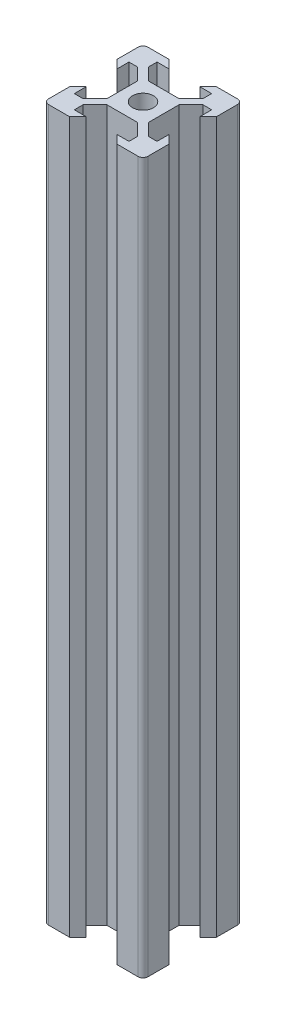
SolidWorks part; units mm, degrees
material "1060 Alloy"
ref_plane "Front Plane" through (0, 0, 0) normal (0, 0, 1) x (1, 0, 0)
ref_plane "Top Plane" through (0, 0, 0) normal (0, 1, 0) x (1, 0, 0)
ref_plane "Right Plane" through (0, 0, 0) normal (1, 0, 0) x (0, 0, -1)
ref_plane "End Plane" through (0, 143, 0) normal (0, 1, 0) x (1, 0, 0)
sketch "MasterLayoutSketch" plane through (0, 0, 0) normal (0, 1, 0) x (1, 0, 0)
  line L0 (-8.325, 3.1) -> (-8.325, 5.5)
  line L1 (-10, -10) -> (10, -10) construction
  line L2 (-10, -10) -> (-10, 10) construction
  line L3 (-10, 10) -> (10, 10) construction
  line L4 (10, -10) -> (10, 10) construction
  line L5 (-10, -10) -> (10, 10) construction
  line L6 (-10, 10) -> (10, -10) construction
  line L7 (-4.775, 10) -> (-3.1, 8.325)
  line L10 (-8.325, 5.5) -> (-6.5607, 5.5)
  line L11 (-10, 4.775) -> (-8.325, 3.1)
  line L12 (-5.5, 8.325) -> (-5.5, 6.5607)
  line L13 (-3.1, 8.325) -> (-5.5, 8.325)
  line L14 (-10, 10) -> (-10, 4.775)
  line L19 (3.1, 8.325) -> (5.5, 8.325)
  line L20 (10, 4.775) -> (8.325, 3.1)
  line L21 (-10, 10) -> (-4.775, 10)
  line L22 (-6.5607, 5.5) -> (-4.1607, 3.1)
  line L23 (-5.5, 6.5607) -> (-3.1, 4.1607)
  line L24 (5.5, 8.325) -> (5.5, 6.5607)
  line L25 (4.775, 10) -> (3.1, 8.325)
  line L26 (8.325, 5.5) -> (6.5607, 5.5)
  line L27 (8.325, 3.1) -> (8.325, 5.5)
  line L28 (10, 10) -> (4.775, 10)
  line L29 (10, 10) -> (10, 4.775)
  line L30 (5.5, 6.5607) -> (3.1, 4.1607)
  line L31 (6.5607, 5.5) -> (4.1607, 3.1)
  line L32 (8.325, -3.1) -> (8.325, -5.5)
  line L33 (4.775, -10) -> (3.1, -8.325)
  line L34 (8.325, -5.5) -> (6.5607, -5.5)
  line L35 (10, -4.775) -> (8.325, -3.1)
  line L36 (5.5, -8.325) -> (5.5, -6.5607)
  line L37 (3.1, -8.325) -> (5.5, -8.325)
  line L38 (10, -10) -> (10, -4.775)
  line L39 (10, -10) -> (4.775, -10)
  line L40 (6.5607, -5.5) -> (4.1607, -3.1)
  line L41 (5.5, -6.5607) -> (3.1, -4.1607)
  line L42 (-3.1, -8.325) -> (-5.5, -8.325)
  line L43 (-10, -4.775) -> (-8.325, -3.1)
  line L44 (-5.5, -8.325) -> (-5.5, -6.5607)
  line L45 (-4.775, -10) -> (-3.1, -8.325)
  line L46 (-8.325, -5.5) -> (-6.5607, -5.5)
  line L47 (-8.325, -3.1) -> (-8.325, -5.5)
  line L48 (-10, -10) -> (-4.775, -10)
  line L49 (-10, -10) -> (-10, -4.775)
  line L50 (-5.5, -6.5607) -> (-3.1, -4.1607)
  line L51 (-6.5607, -5.5) -> (-4.1607, -3.1)
  line L52 (-4.1607, 3.1) -> (-4.1607, -3.1)
  line L53 (-3.1, -4.1607) -> (3.1, -4.1607)
  line L54 (4.1607, -3.1) -> (4.1607, 3.1)
  line L55 (-3.1, 4.1607) -> (3.1, 4.1607)
  circle A0 centre (0, 0) radius 2.1
  point P0 (0, 0)
  point P9 (0, 0)
  dimension "D6" = 4.2
  dimension "D1" = 20
  dimension "D2" = 4
  dimension "D3" = 11
  dimension "D4" = 9.55
  dimension "D5" = 6.2
  dimension "D7" = 1.5
extrude "Main Extrusion" add sketch "MasterLayoutSketch" along normal up to surface (143 mm away) up to plane "End Plane"
fillet "Edge Fillets" radius 1 4 edges at (10, 71.5, -10) (10, 71.5, 10) (-10, 71.5, 10) (-10, 71.5, -10)
